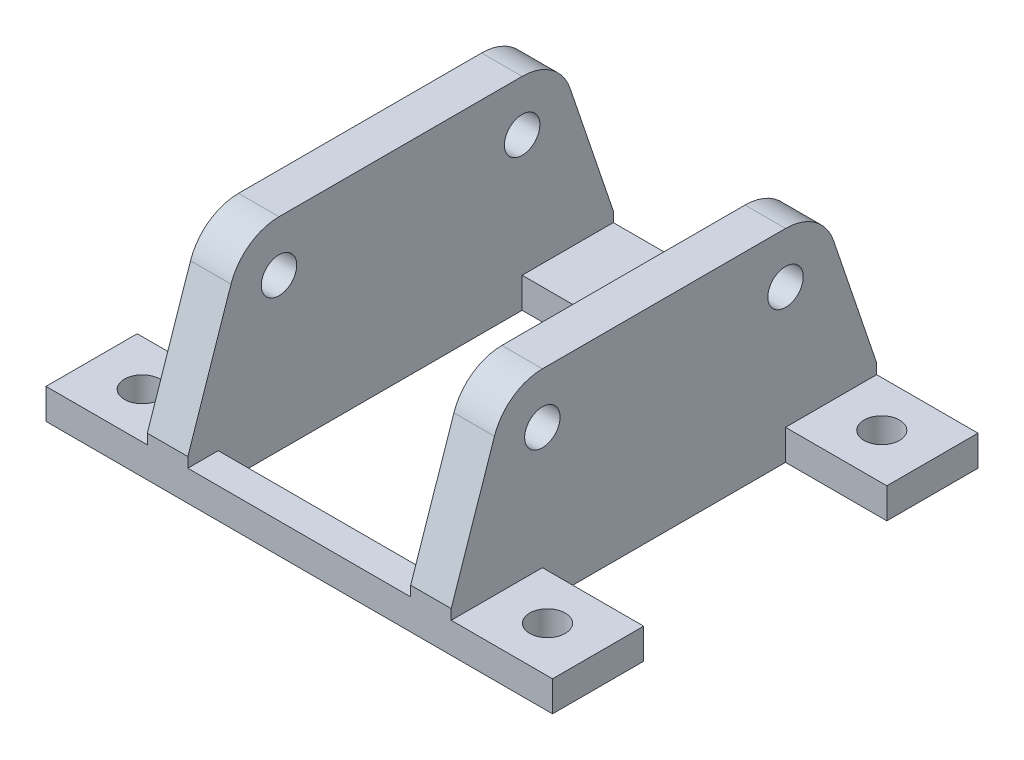
SolidWorks part; units mm, degrees
ref_plane "Plano frontal" through (0, 0, 0) normal (0, 0, 1) x (1, 0, 0)
ref_plane "Plano superior" through (0, 0, 0) normal (0, 1, 0) x (1, 0, 0)
ref_plane "Plano direito" through (0, 0, 0) normal (1, 0, 0) x (0, 0, -1)
sketch "Esboço1" plane through (0, 0, 0) normal (0, 1, 0) x (1, 0, 0)
  line L0 (-15, 25) -> (15, 25)
  line L1 (-11, 21) -> (11, 21)
  line L2 (-11, 21) -> (-11, -21)
  line L3 (-11, -21) -> (11, -21)
  line L4 (11, 21) -> (11, -21)
  line L5 (-11, 21) -> (11, -21) construction
  line L6 (-11, -21) -> (11, 21) construction
  line L7 (15, 25) -> (15, -25)
  line L8 (-15, -25) -> (15, -25)
  line L9 (-15, 25) -> (-15, -25)
  line L10 (-4, 7) -> (4, 7) construction
  line L11 (4, 7) -> (4, 17) construction
  line L12 (4, 17) -> (-4, 17) construction
  line L13 (-4, 17) -> (-4, 7) construction
  line L14 (-11, 0) -> (11, 0) construction
  line L15 (-4, -17) -> (-4, -7) construction
  line L16 (4, -17) -> (-4, -17) construction
  line L17 (4, -7) -> (4, -17) construction
  line L18 (-4, -7) -> (4, -7) construction
  point P0 (0, 0)
  point P12 (0, 7)
  dimension "D2" = 30
  dimension "D3" = 10
  dimension "D4" = 8
  dimension "D5" = 50
  dimension "D6" = 14
  dimension "D1" = 4
extrude "Ressalto-extrusão1" add sketch "Esboço1" along normal blind 20
sketch "Esboço3" plane through (15, 0, 0) normal (1, 0, 0) x (0, 0, -1)
  line L0 (0, 0) -> (0, 23.3091) construction
  line L1 (-25, 0) -> (25, 0) construction
  line L2 (-12, 15) -> (12, 15) construction
  line L3 (-25, 20) -> (25, 20) construction
  circle A0 centre (-12, 15) radius 1.75
  circle A1 centre (12, 15) radius 1.75
  circle A2 centre (-12, 15) radius 5 construction
  circle A3 centre (12, 15) radius 5 construction
  point P8 (0, 15)
  dimension "D1" = 10
  dimension "D2" = 3.5
  dimension "D3" = 14
  dimension "D4" = 5
extrude "Corte-extrusão2" cut sketch "Esboço3" against normal through all
sketch "Esboço5" plane through (-15, 0, 0) normal (-1, 0, 0) x (0, 0, 1)
  line L0 (-16.7363, 16.6024) -> (-21, 4)
  line L2 (-25, 0) -> (25, 0) construction
  line L3 (25, 0) -> (25, 4)
  line L4 (0, 0) -> (0, 20) construction
  line L5 (-25, 20) -> (25, 20) construction
  line L6 (21, 0) -> (25, 0)
  line L7 (-25, 20) -> (-12, 20)
  line L8 (-25, 20) -> (-25, 4)
  line L9 (21, 4) -> (21, 0)
  line L10 (25, 20) -> (25, 4)
  line L11 (25, 20) -> (12, 20)
  line L12 (-21, 4) -> (-21, 0)
  line L13 (-21, 0) -> (-25, 0)
  line L14 (-25, 0) -> (-25, 4)
  line L15 (16.7363, 16.6024) -> (21, 4)
  arc A0 (-12, 20) -> (-16.7363, 16.6024) centre (-12, 15) ccw
  arc A1 (12, 20) -> (16.7363, 16.6024) centre (12, 15) cw
  dimension "D1" = 4
  dimension "D2" = 4
extrude "Corte-extrusão3" cut sketch "Esboço5" against normal through all both and the other way through all
sketch "Esboço6" plane through (0, 0, 0) normal (0, -1, 0) x (1, 0, 0)
  line L0 (-15, 21) -> (15, 21)
  line L2 (15, 21) -> (15, -21) construction
  line L3 (15, 18) -> (-15, 18)
  line L4 (-15, -21) -> (-15, 21) construction
  line L6 (25, -21) -> (25, -12)
  line L7 (25, -12) -> (-25, -12)
  line L8 (-25, -12) -> (-25, -21)
  line L9 (-25, -21) -> (25, -21)
  line L10 (-11, -21) -> (-15, -21) construction
  line L11 (0, 0) -> (0, -6.5328) construction
  line L12 (0, 0) -> (-18.8461, 0) construction
  line L13 (-15, 21) -> (-25, 21)
  line L14 (-25, 21) -> (-25, 12)
  line L15 (-25, 12) -> (-15, 12)
  line L16 (15, 12) -> (25, 12)
  line L17 (25, 12) -> (25, 21)
  line L18 (25, 21) -> (15, 21)
  line L20 (-15, 18) -> (-15, 12)
  line L21 (15, 12) -> (15, 18)
  circle A0 centre (-20, -16.5) radius 1.75
  circle A1 centre (20, -16.5) radius 1.75
  circle A2 centre (20, 16.5) radius 1.75
  circle A3 centre (-20, 16.5) radius 1.75
  point P13 (0, -12)
  point P26 (-25, -16.5)
  point P37 (-25, 16.5)
  dimension "D4" = 3.5
  dimension "D1" = 9
  dimension "D2" = 50
  dimension "D3" = 40
  dimension "D5" = 3
extrude "Ressalto-extrusão2" add sketch "Esboço6" against normal blind 3
